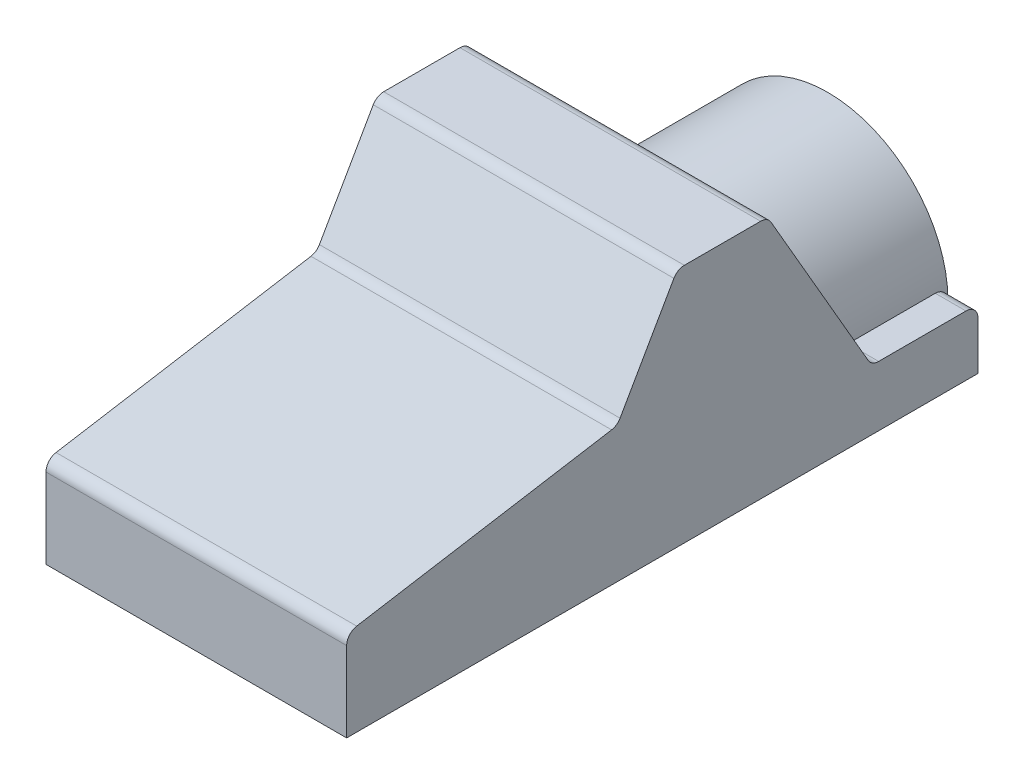
SolidWorks part; units mm, degrees
ref_plane "Front Plane" through (0, 0, 0) normal (0, 0, 1) x (1, 0, 0)
ref_plane "Top Plane" through (0, 0, 0) normal (0, 1, 0) x (1, 0, 0)
ref_plane "Right Plane" through (0, 0, 0) normal (1, 0, 0) x (0, 0, -1)
sketch "Sketch1" plane through (0, 0, 0) normal (1, 0, 0) x (0, 0, -1)
  line L0 (0, 0) -> (-133.35, 0)
  line L1 (-133.35, 0) -> (-133.35, 16.8983)
  line L2 (-131.2276, 19.4037) -> (-77.3895, 28.3768)
  line L3 (-75.6017, 29.622) -> (-64.2313, 49.5202)
  line L4 (-62.026, 50.8) -> (-45.9165, 50.8)
  line L5 (-43.7168, 49.53) -> (-23.1862, 13.97)
  line L6 (-20.9865, 12.7) -> (-2.54, 12.7)
  line L7 (0, 10.16) -> (0, 0)
  line L8 (-44.45, 50.8) -> (-44.45, -41.6092) construction
  arc A0 (-45.9165, 50.8) -> (-43.7168, 49.53) centre (-45.9165, 48.26) cw
  arc A1 (-64.2313, 49.5202) -> (-62.026, 50.8) centre (-62.026, 48.26) cw
  arc A2 (-77.3895, 28.3768) -> (-75.6017, 29.622) centre (-77.8071, 30.8822) ccw
  arc A3 (-133.35, 16.8983) -> (-131.2276, 19.4037) centre (-130.81, 16.8983) cw
  arc A4 (-2.54, 12.7) -> (0, 10.16) centre (-2.54, 10.16) cw
  arc A5 (-23.1862, 13.97) -> (-20.9865, 12.7) centre (-20.9865, 15.24) ccw
  point P7 (0, 5.08)
  point P16 (-63.5, 50.8)
  point P19 (-76.2, 28.575)
  point P22 (-133.35, 19.05)
  point P25 (0, 12.7)
  point P28 (-22.453, 12.7)
  dimension "D10" = 2.54
  dimension "D1" = 133.35
  dimension "D2" = 19.05
  dimension "D3" = 57.15
  dimension "D4" = 19.05
  dimension "D5" = 44.45
  dimension "D6" = 38.1
  dimension "D7" = 30
  dimension "D8" = 12.7
  dimension "D9" = 28.575
extrude "Boss-Extrude1" add sketch "Sketch1" along normal mid plane 63.5
sketch "Sketch2" plane through (0, 0, 0) normal (0, 0, -1) x (-1, 0, 0)
  line L1 (-31.75, 0) -> (31.75, 0) construction
  line L3 (-31.75, 10.16) -> (31.75, 10.16) construction
  line L5 (-12.7, 0) -> (12.7, 0)
  line L8 (-12.7, 0) -> (-31.75, 0)
  line L9 (-31.75, 0) -> (-31.75, 10.16)
  line L10 (-31.75, 10.16) -> (-25.4, 10.16)
  line L11 (25.4, 10.16) -> (31.75, 10.16)
  line L12 (31.75, 10.16) -> (31.75, 0)
  line L13 (31.75, 0) -> (12.7, 0)
  arc A1 (-25.4, 10.16) -> (25.4, 10.16) centre (0, 10.16) cw
  point P12 (0, 35.56)
  dimension "D2" = 25.4
extrude "Boss-Extrude2" add sketch "Sketch2" against normal up to next
sketch "Sketch3" plane through (0, 0, 0) normal (0, 0, -1) x (-1, 0, 0)
  line L0 (-12.7, 0) -> (12.7, 0)
  line L1 (-31.75, 0) -> (31.75, 0) construction
  line L2 (12.7, 0) -> (12.7, 12.7)
  line L3 (-12.7, 12.7) -> (-12.7, 0)
  arc A0 (12.7, 12.7) -> (-12.7, 12.7) centre (0, 12.7) ccw
  point P7 (0, 0)
  dimension "D2" = 12.7
  dimension "D1" = 25.4
extrude "Cut-Extrude1" cut sketch "Sketch3" against normal blind 53.975
